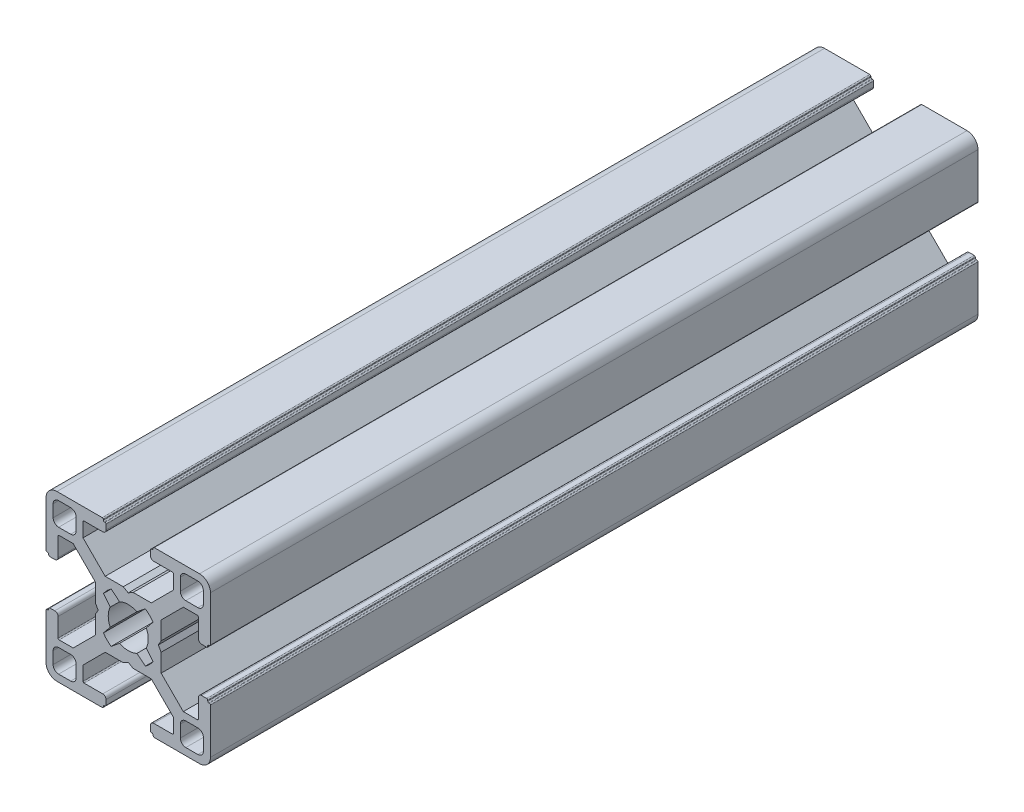
SolidWorks part; units mm, degrees
material "6063 Aluminum Alloy"
ref_plane "Płaszczyzna przednia" through (0, 0, 0) normal (0, 0, 1) x (1, 0, 0)
ref_plane "Płaszczyzna górna" through (0, 0, 0) normal (0, 1, 0) x (1, 0, 0)
ref_plane "Płaszczyzna prawa" through (0, 0, 0) normal (1, 0, 0) x (0, 0, -1)
sketch "Szkic1" plane through (0, 0, 0) normal (0, 0, 1) x (1, 0, 0)
  line L0 (12.7, 13.7) -> (10.5, 13.7)
  line L1 (9.5, 12.7) -> (9.5, 10.5)
  line L2 (10.5, 9.5) -> (12.7, 9.5)
  line L3 (13.7, 10.5) -> (13.7, 12.7)
  line L4 (-1.5829, 3.2889) -> (-3.1172, 4.5314)
  line L5 (-4.5314, 3.1172) -> (-3.2889, 1.5829)
  line L6 (-3.2889, -1.5829) -> (-4.5314, -3.1172)
  line L7 (-3.1172, -4.5314) -> (-1.5829, -3.2889)
  line L8 (1.5829, -3.2889) -> (3.1172, -4.5314)
  line L9 (4.5314, -3.1172) -> (3.2889, -1.5829)
  line L10 (3.2889, 1.5829) -> (4.5314, 3.1172)
  line L11 (3.1172, 4.5314) -> (1.5829, 3.2889)
  line L12 (-12.7, -13.7) -> (-10.5, -13.7)
  line L13 (-9.5, -12.7) -> (-9.5, -10.5)
  line L14 (-10.5, -9.5) -> (-12.7, -9.5)
  line L15 (-13.7, -10.5) -> (-13.7, -12.7)
  line L16 (13.7, -12.7) -> (13.7, -10.5)
  line L17 (12.7, -9.5) -> (10.5, -9.5)
  line L18 (9.5, -10.5) -> (9.5, -12.7)
  line L19 (-10.5, 13.7) -> (-12.7, 13.7)
  line L20 (-13.7, 12.7) -> (-13.7, 10.5)
  line L21 (-12.7, 9.5) -> (-10.5, 9.5)
  line L22 (-9.5, 10.5) -> (-9.5, 12.7)
  line L23 (10.5, -13.7) -> (12.7, -13.7)
  line L24 (0, -5.48) -> (0.9007, -6)
  line L25 (0.9007, -6) -> (4.2039, -6)
  line L26 (4.2039, -6) -> (8.25, -10.0461)
  line L27 (8.25, -10.0461) -> (8.25, -12.6)
  line L28 (8.05, -12.8) -> (4.65, -12.8)
  line L29 (4.05, -13.4) -> (4.05, -14.3)
  line L30 (4.25, -14.5) -> (4.35, -14.5)
  line L31 (4.55, -14.7) -> (4.55, -14.8)
  line L32 (4.75, -15) -> (13, -15)
  line L33 (15, -13) -> (15, -4.75)
  line L34 (14.8, -4.55) -> (14.7, -4.55)
  line L35 (14.5, -4.35) -> (14.5, -4.25)
  line L36 (14.3, -4.05) -> (13.4, -4.05)
  line L37 (12.8, -4.65) -> (12.8, -8.05)
  line L38 (12.6, -8.25) -> (10.0461, -8.25)
  line L39 (10.0461, -8.25) -> (6, -4.2039)
  line L40 (6, -4.2039) -> (6, -0.9007)
  line L41 (6, -0.9007) -> (5.48, 0)
  line L42 (5.48, 0) -> (6, 0.9007)
  line L43 (6, 0.9007) -> (6, 4.2039)
  line L44 (6, 4.2039) -> (10.0461, 8.25)
  line L45 (10.0461, 8.25) -> (12.6, 8.25)
  line L46 (12.8, 8.05) -> (12.8, 4.65)
  line L47 (13.4, 4.05) -> (14.3, 4.05)
  line L48 (14.5, 4.25) -> (14.5, 4.35)
  line L49 (14.7, 4.55) -> (14.8, 4.55)
  line L50 (15, 4.75) -> (15, 13)
  line L51 (13, 15) -> (4.75, 15)
  line L52 (4.55, 14.8) -> (4.55, 14.7)
  line L53 (4.35, 14.5) -> (4.25, 14.5)
  line L54 (4.05, 14.3) -> (4.05, 13.4)
  line L55 (4.65, 12.8) -> (8.05, 12.8)
  line L56 (8.25, 12.6) -> (8.25, 10.0461)
  line L57 (8.25, 10.0461) -> (4.2039, 6)
  line L58 (4.2039, 6) -> (0.9007, 6)
  line L59 (0.9007, 6) -> (0, 5.48)
  line L60 (0, 5.48) -> (-0.9007, 6)
  line L61 (-0.9007, 6) -> (-4.2039, 6)
  line L62 (-4.2039, 6) -> (-8.25, 10.0461)
  line L63 (-8.25, 10.0461) -> (-8.25, 12.6)
  line L64 (-8.05, 12.8) -> (-4.65, 12.8)
  line L65 (-4.05, 13.4) -> (-4.05, 14.3)
  line L66 (-4.25, 14.5) -> (-4.35, 14.5)
  line L67 (-4.55, 14.7) -> (-4.55, 14.8)
  line L68 (-4.75, 15) -> (-13, 15)
  line L69 (-15, 13) -> (-15, 4.75)
  line L70 (-14.8, 4.55) -> (-14.7, 4.55)
  line L71 (-14.5, 4.35) -> (-14.5, 4.25)
  line L72 (-14.3, 4.05) -> (-13.4, 4.05)
  line L73 (-12.8, 4.65) -> (-12.8, 8.05)
  line L74 (-12.6, 8.25) -> (-10.0461, 8.25)
  line L75 (-10.0461, 8.25) -> (-6, 4.2039)
  line L76 (-6, 4.2039) -> (-6, 0.9007)
  line L77 (-6, 0.9007) -> (-5.48, 0)
  line L78 (-5.48, 0) -> (-6, -0.9007)
  line L79 (-6, -0.9007) -> (-6, -4.2039)
  line L80 (-6, -4.2039) -> (-10.0461, -8.25)
  line L81 (-10.0461, -8.25) -> (-12.6, -8.25)
  line L82 (-12.8, -8.05) -> (-12.8, -4.65)
  line L83 (-13.4, -4.05) -> (-14.3, -4.05)
  line L84 (-14.5, -4.25) -> (-14.5, -4.35)
  line L85 (-14.7, -4.55) -> (-14.8, -4.55)
  line L86 (-15, -4.75) -> (-15, -13)
  line L87 (-13, -15) -> (-4.75, -15)
  line L88 (-4.55, -14.8) -> (-4.55, -14.7)
  line L89 (-4.35, -14.5) -> (-4.25, -14.5)
  line L90 (-4.05, -14.3) -> (-4.05, -13.4)
  line L91 (-4.65, -12.8) -> (-8.05, -12.8)
  line L92 (-8.25, -12.6) -> (-8.25, -10.0461)
  line L93 (-8.25, -10.0461) -> (-4.2039, -6)
  line L94 (-4.2039, -6) -> (-0.9007, -6)
  line L95 (-0.9007, -6) -> (0, -5.48)
  line L96 (-3.8891, -3.8891) -> (3.8891, 3.8891) construction
  line L97 (-3.8891, 3.8891) -> (3.8891, -3.8891) construction
  line L98 (55, 0) -> (-55, 0) construction
  arc A0 (10.5, 13.7) -> (9.5, 12.7) centre (10.5, 12.7) ccw
  arc A1 (9.5, 10.5) -> (10.5, 9.5) centre (10.5, 10.5) ccw
  arc A2 (12.7, 9.5) -> (13.7, 10.5) centre (12.7, 10.5) ccw
  arc A3 (13.7, 12.7) -> (12.7, 13.7) centre (12.7, 12.7) ccw
  arc A4 (-3.1172, 4.5314) -> (-4.5314, 3.1172) centre (0, 0) ccw
  arc A5 (-3.2889, 1.5829) -> (-3.2889, -1.5829) centre (0, 0) ccw
  arc A6 (-4.5314, -3.1172) -> (-3.1172, -4.5314) centre (0, 0) ccw
  arc A7 (-1.5829, -3.2889) -> (1.5829, -3.2889) centre (0, 0) ccw
  arc A8 (3.1172, -4.5314) -> (4.5314, -3.1172) centre (0, 0) ccw
  arc A9 (3.2889, -1.5829) -> (3.2889, 1.5829) centre (0, 0) ccw
  arc A10 (4.5314, 3.1172) -> (3.1172, 4.5314) centre (0, 0) ccw
  arc A11 (1.5829, 3.2889) -> (-1.5829, 3.2889) centre (0, 0) ccw
  arc A12 (-10.5, -13.7) -> (-9.5, -12.7) centre (-10.5, -12.7) ccw
  arc A13 (-9.5, -10.5) -> (-10.5, -9.5) centre (-10.5, -10.5) ccw
  arc A14 (-12.7, -9.5) -> (-13.7, -10.5) centre (-12.7, -10.5) ccw
  arc A15 (-13.7, -12.7) -> (-12.7, -13.7) centre (-12.7, -12.7) ccw
  arc A16 (12.7, -13.7) -> (13.7, -12.7) centre (12.7, -12.7) ccw
  arc A17 (13.7, -10.5) -> (12.7, -9.5) centre (12.7, -10.5) ccw
  arc A18 (10.5, -9.5) -> (9.5, -10.5) centre (10.5, -10.5) ccw
  arc A19 (9.5, -12.7) -> (10.5, -13.7) centre (10.5, -12.7) ccw
  arc A20 (-12.7, 13.7) -> (-13.7, 12.7) centre (-12.7, 12.7) ccw
  arc A21 (-13.7, 10.5) -> (-12.7, 9.5) centre (-12.7, 10.5) ccw
  arc A22 (-10.5, 9.5) -> (-9.5, 10.5) centre (-10.5, 10.5) ccw
  arc A23 (-9.5, 12.7) -> (-10.5, 13.7) centre (-10.5, 12.7) ccw
  arc A24 (8.05, -12.8) -> (8.25, -12.6) centre (8.05, -12.6) ccw
  arc A25 (4.65, -12.8) -> (4.05, -13.4) centre (4.65, -13.4) ccw
  arc A26 (4.05, -14.3) -> (4.25, -14.5) centre (4.25, -14.3) ccw
  arc A27 (4.55, -14.7) -> (4.35, -14.5) centre (4.35, -14.7) ccw
  arc A28 (4.55, -14.8) -> (4.75, -15) centre (4.75, -14.8) ccw
  arc A29 (13, -15) -> (15, -13) centre (13, -13) ccw
  arc A30 (15, -4.75) -> (14.8, -4.55) centre (14.8, -4.75) ccw
  arc A31 (14.5, -4.35) -> (14.7, -4.55) centre (14.7, -4.35) ccw
  arc A32 (14.5, -4.25) -> (14.3, -4.05) centre (14.3, -4.25) ccw
  arc A33 (13.4, -4.05) -> (12.8, -4.65) centre (13.4, -4.65) ccw
  arc A34 (12.6, -8.25) -> (12.8, -8.05) centre (12.6, -8.05) ccw
  arc A35 (12.8, 8.05) -> (12.6, 8.25) centre (12.6, 8.05) ccw
  arc A36 (12.8, 4.65) -> (13.4, 4.05) centre (13.4, 4.65) ccw
  arc A37 (14.3, 4.05) -> (14.5, 4.25) centre (14.3, 4.25) ccw
  arc A38 (14.7, 4.55) -> (14.5, 4.35) centre (14.7, 4.35) ccw
  arc A39 (14.8, 4.55) -> (15, 4.75) centre (14.8, 4.75) ccw
  arc A40 (15, 13) -> (13, 15) centre (13, 13) ccw
  arc A41 (4.75, 15) -> (4.55, 14.8) centre (4.75, 14.8) ccw
  arc A42 (4.35, 14.5) -> (4.55, 14.7) centre (4.35, 14.7) ccw
  arc A43 (4.25, 14.5) -> (4.05, 14.3) centre (4.25, 14.3) ccw
  arc A44 (4.05, 13.4) -> (4.65, 12.8) centre (4.65, 13.4) ccw
  arc A45 (8.25, 12.6) -> (8.05, 12.8) centre (8.05, 12.6) ccw
  arc A46 (-8.05, 12.8) -> (-8.25, 12.6) centre (-8.05, 12.6) ccw
  arc A47 (-4.65, 12.8) -> (-4.05, 13.4) centre (-4.65, 13.4) ccw
  arc A48 (-4.05, 14.3) -> (-4.25, 14.5) centre (-4.25, 14.3) ccw
  arc A49 (-4.55, 14.7) -> (-4.35, 14.5) centre (-4.35, 14.7) ccw
  arc A50 (-4.55, 14.8) -> (-4.75, 15) centre (-4.75, 14.8) ccw
  arc A51 (-13, 15) -> (-15, 13) centre (-13, 13) ccw
  arc A52 (-15, 4.75) -> (-14.8, 4.55) centre (-14.8, 4.75) ccw
  arc A53 (-14.5, 4.35) -> (-14.7, 4.55) centre (-14.7, 4.35) ccw
  arc A54 (-14.5, 4.25) -> (-14.3, 4.05) centre (-14.3, 4.25) ccw
  arc A55 (-13.4, 4.05) -> (-12.8, 4.65) centre (-13.4, 4.65) ccw
  arc A56 (-12.6, 8.25) -> (-12.8, 8.05) centre (-12.6, 8.05) ccw
  arc A57 (-12.8, -8.05) -> (-12.6, -8.25) centre (-12.6, -8.05) ccw
  arc A58 (-12.8, -4.65) -> (-13.4, -4.05) centre (-13.4, -4.65) ccw
  arc A59 (-14.3, -4.05) -> (-14.5, -4.25) centre (-14.3, -4.25) ccw
  arc A60 (-14.7, -4.55) -> (-14.5, -4.35) centre (-14.7, -4.35) ccw
  arc A61 (-14.8, -4.55) -> (-15, -4.75) centre (-14.8, -4.75) ccw
  arc A62 (-15, -13) -> (-13, -15) centre (-13, -13) ccw
  arc A63 (-4.75, -15) -> (-4.55, -14.8) centre (-4.75, -14.8) ccw
  arc A64 (-4.35, -14.5) -> (-4.55, -14.7) centre (-4.35, -14.7) ccw
  arc A65 (-4.25, -14.5) -> (-4.05, -14.3) centre (-4.25, -14.3) ccw
  arc A66 (-4.05, -13.4) -> (-4.65, -12.8) centre (-4.65, -13.4) ccw
  arc A67 (-8.25, -12.6) -> (-8.05, -12.8) centre (-8.05, -12.6) ccw
  dimension "D1" = 3.65
  dimension "D7" = 2
  dimension "D9" = 3.65
  dimension "D10" = 5.5
  dimension "D23" = 1
  dimension "D37" = 0.2
  dimension "D59" = 0.6
  dimension "D60" = 0.2
  dimension "D63" = 0.2
  dimension "D64" = 0.2
  dimension "D67" = 0.2
  dimension "D68" = 0.2
  dimension "D69" = 0.2
  dimension "D73" = 0.2
  dimension "D75" = 0.2
  dimension "D76" = 0.2
  dimension "D2" = 30
  dimension "D3" = 30
  dimension "D4" = 8.1
  dimension "D5" = 15
  dimension "D6" = 15
  dimension "D8" = 4.05
  dimension "D11" = 45
  dimension "D12" = 6
  dimension "D13" = 2
  dimension "D14" = 12
  dimension "D15" = 6
  dimension "D16" = 12
  dimension "D17" = 6
  dimension "D18" = 12
  dimension "D19" = 6
  dimension "D20" = 12
  dimension "D21" = 1.3
  dimension "D22" = 1.3
  dimension "D24" = 1.3
  dimension "D25" = 4.2
  dimension "D26" = 4.2
  dimension "D27" = 4.2
  dimension "D28" = 1.3
  dimension "D29" = 4.2
  dimension "D30" = 16.5
  dimension "D31" = 8.25
  dimension "D32" = 2.54
  dimension "D33" = 1.27
  dimension "D34" = 2.54
  dimension "D35" = 1.27
  dimension "D36" = 2.2
  dimension "D38" = 2.2
  dimension "D39" = 2.2
  dimension "D40" = 6
  dimension "D41" = 6
  dimension "D42" = 12
  dimension "D43" = 2
  dimension "D44" = 2
  dimension "D45" = 2
  dimension "D46" = 2.2
  dimension "D47" = 16.5
  dimension "D48" = 8.25
  dimension "D49" = 6
  dimension "D50" = 8.1
  dimension "D51" = 4.05
  dimension "D52" = 0.52
  dimension "D53" = 120
  dimension "D54" = 60
  dimension "D55" = 0.52
  dimension "D56" = 0.52
  dimension "D57" = 0.52
  dimension "D58" = 120
  dimension "D61" = 0.5
  dimension "D62" = 0.5
  dimension "D65" = 0.5
  dimension "D66" = 0.5
  dimension "D70" = 0.5
  dimension "D71" = 0.5
  dimension "D72" = 0.5
  dimension "D74" = 0.5
extrude "Dodanie-wyciągnięcie1" add sketch "Szkic1" along normal mid plane 140
equation "\"D5@Szkic1\"=\"D2@Szkic1\"/2"
equation "\"D6@Szkic1\"=\"D3@Szkic1\"/2"
equation "\"D8@Szkic1\"=\"D4@Szkic1\"/2"
equation "\"D14@Szkic1\"=\"D12@Szkic1\"*2"
equation "\"D15@Szkic1\"=\"D12@Szkic1\""
equation "\"D17@Szkic1\"=\"D12@Szkic1\""
equation "\"D19@Szkic1\"=\"D12@Szkic1\""
equation "\"D31@Szkic1\"=\"D30@Szkic1\"/2"
equation "\"D33@Szkic1\"=\"D32@Szkic1\"/2"
equation "\"D35@Szkic1\"=\"D34@Szkic1\"/2"
equation "\"D42@Szkic1\"=\"D40@Szkic1\"*2"
equation "\"D46@Szkic1\"=\"D36@Szkic1\""
equation "\"D47@Szkic1\"=\"D30@Szkic1\""
equation "\"D48@Szkic1\"=\"D31@Szkic1\""
equation "\"D51@Szkic1\"=\"D50@Szkic1\"/2"
equation "\"D54@Szkic1\"=\"D53@Szkic1\"/2"
equation "\"D55@Szkic1\"=\"D52@Szkic1\""
equation "\"D56@Szkic1\"=\"D52@Szkic1\""
equation "\"D57@Szkic1\"=\"D52@Szkic1\""
